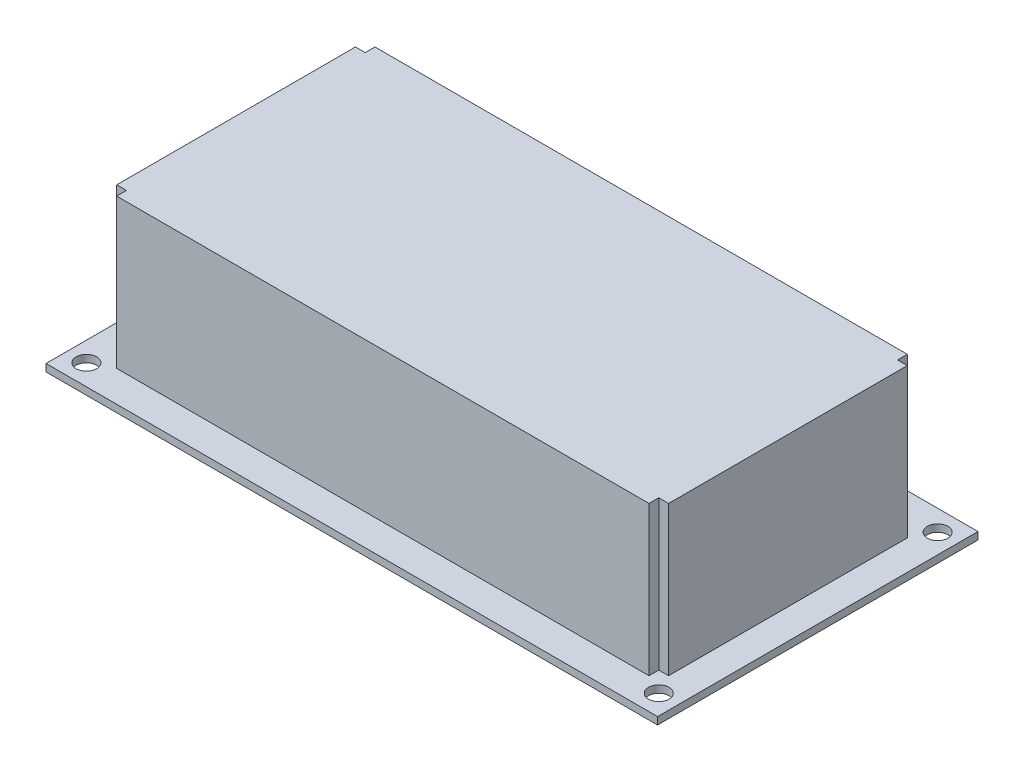
SolidWorks part; units mm, degrees
ref_plane "Спереди" through (0, 0, 0) normal (0, 0, 1) x (1, 0, 0)
ref_plane "Сверху" through (0, 0, 0) normal (0, 1, 0) x (1, 0, 0)
ref_plane "Справа" through (0, 0, 0) normal (1, 0, 0) x (0, 0, -1)
sketch "Эскиз1" plane through (0, 0, 0) normal (0, 1, 0) x (1, 0, 0)
  line L1 (-62.5, -32.75) -> (62.5, -32.75)
  line L2 (-62.5, -32.75) -> (-62.5, 32.75)
  line L3 (-62.5, 32.75) -> (62.5, 32.75)
  line L4 (62.5, -32.75) -> (62.5, 32.75)
  line L5 (-62.5, -32.75) -> (62.5, 32.75) construction
  line L6 (-62.5, 32.75) -> (62.5, -32.75) construction
  point P0 (0, 0)
  dimension "D1" = 125
  dimension "D2" = 65.5
extrude "Бобышка-Вытянуть1" add sketch "Эскиз1" along normal blind 1.5
sketch "Эскиз2" plane through (0, 1.5, 0) normal (0, 1, 0) x (1, 0, 0)
  line L1 (-58.5, -28.5) -> (58.5, -28.5)
  line L2 (-58.5, -28.5) -> (-58.5, 28.5)
  line L3 (-58.5, 28.5) -> (58.5, 28.5)
  line L4 (58.5, -28.5) -> (58.5, 28.5)
  line L5 (-58.5, -28.5) -> (58.5, 28.5) construction
  line L6 (-58.5, 28.5) -> (58.5, -28.5) construction
  point P0 (0, 0)
  dimension "D1" = 57
  dimension "D2" = 117
hole_wizard "Сверло под метчик  спиральное M41" positions "Эскиз3" profile "Эскиз5" hole size "M4x0.7" standard "DIN" end condition up to next
sketch "Эскиз3" plane through (0, 1.5, 0) normal (0, 1, 0) x (1, 0, 0)
  point P0 (-58.5, -28.5)
  point P3 (-58.5, 28.5)
  point P6 (58.5, 28.5)
  point P9 (58.5, -28.5)
sketch "Эскиз5" plane through (-58.5, 1.5, 28.5) normal (1, 0, 0) x (0, 0, 1)
  line L0 (0, 0) -> (0, 1.5)
  line L1 (0, 1.5) -> (2.1, 1.5)
  line L2 (2.1, 1.5) -> (2.1, 0)
  line L5 (2.1, 0) -> (0, 0)
  line L11 (0, -6.35) -> (0, 107.95) construction
  dimension "Диаметр сквозного отверстия" = 4.2
  dimension "Глубина сквозного отверстия" = 1.5
sketch "Эскиз6" plane through (0, 1.5, 0) normal (0, 1, 0) x (1, 0, 0)
  line L0 (56.4, -24.4) -> (54.4, -24.4)
  line L1 (-54.4, -26.4) -> (54.4, -26.4)
  line L2 (-56.4, -24.4) -> (-56.4, 24.4)
  line L3 (-54.4, 26.4) -> (54.4, 26.4)
  line L4 (56.4, -24.4) -> (56.4, 24.4)
  line L5 (-56.4, -26.4) -> (56.4, 26.4) construction
  line L6 (-56.4, 26.4) -> (56.4, -26.4) construction
  line L7 (54.4, -24.4) -> (54.4, -26.4)
  line L8 (56.4, 24.4) -> (54.4, 24.4)
  line L9 (54.4, 24.4) -> (54.4, 26.4)
  line L10 (-56.4, 24.4) -> (-54.4, 24.4)
  line L11 (-54.4, 24.4) -> (-54.4, 26.4)
  line L12 (-56.4, -24.4) -> (-54.4, -24.4)
  line L13 (-54.4, -24.4) -> (-54.4, -26.4)
  point P0 (0, 0)
  dimension "D1" = 2
extrude "Бобышка-Вытянуть2" add sketch "Эскиз6" along normal blind 30.5
